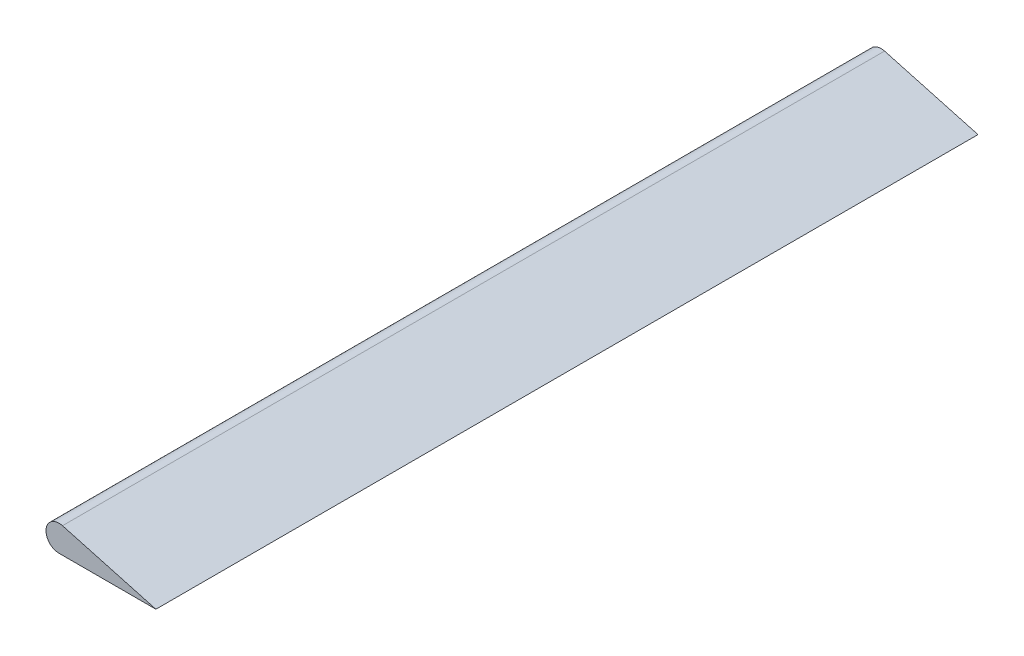
SolidWorks part; units mm, degrees
ref_plane "Front Plane" through (0, 0, 0) normal (0, 0, 1) x (1, 0, 0)
ref_plane "Top Plane" through (0, 0, 0) normal (0, 1, 0) x (1, 0, 0)
ref_plane "Right Plane" through (0, 0, 0) normal (1, 0, 0) x (0, 0, -1)
sketch "Sketch2" plane through (0, 0, -3) normal (0, 0, 1) x (1, 0, 0)
  line L0 (442.7178, 24.3712) -> (474.4331, 20.1125) construction
  line L1 (442.557, 28.8563) -> (474.4331, 20.1125) construction
  line L4 (446.392, 20.1125) -> (474.4331, 20.1125)
  line L5 (474.4331, 20.1125) -> (447.3909, 27.5303)
  line L6 (474.4331, 20.1125) -> (441.3938, 20.1125) construction
  arc A1 (447.3909, 27.5303) -> (446.392, 20.1125) centre (446.392, 23.8886) ccw
extrude "Boss-Extrude1" add sketch "Sketch2" along normal blind 238
sketch "Sketch3" plane through (0, -30.5897, 0) normal (0, -1, 0) x (1, 0, 0)
  line L0 (442.6158, 235) -> (442.6158, -3) construction
  line L1 (442.6158, 190) -> (457.6158, 190)
  line L2 (442.6158, 190) -> (442.6158, 175)
  line L3 (442.6158, 175) -> (457.6158, 175)
  line L4 (457.6158, 190) -> (457.6158, 175)
  line L5 (446.392, -3) -> (474.4331, -3) construction
  line L6 (442.6158, 42) -> (457.6158, 42)
  line L7 (442.6158, 42) -> (442.6158, 57)
  line L8 (442.6158, 57) -> (457.6158, 57)
  line L9 (457.6158, 42) -> (457.6158, 57)
  line L10 (446.392, 235) -> (474.4331, 235) construction
  dimension "D1" = 15
  dimension "D2" = 15
  dimension "D3" = 45
  dimension "D4" = 15
  dimension "D5" = 15
  dimension "D6" = 45
extrude "Cut-Extrude1" cut sketch "Sketch3" against normal blind 54
